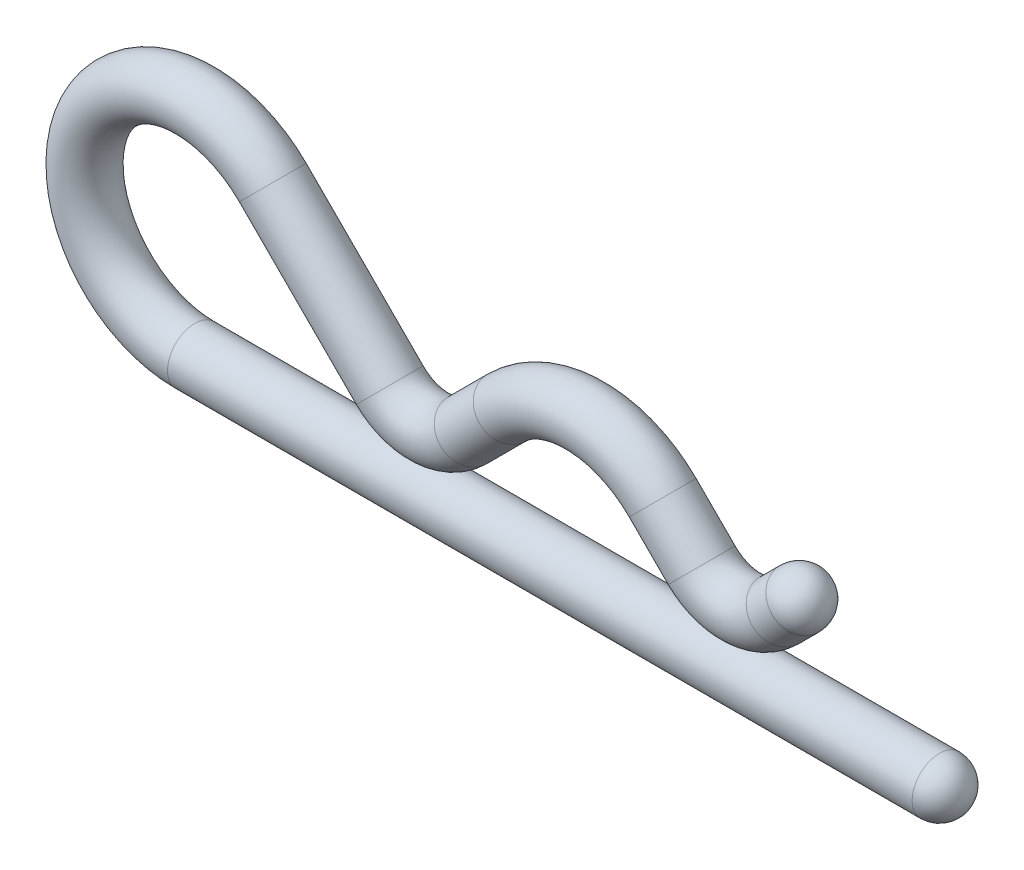
SolidWorks part; units mm, degrees
ref_plane "Front Plane" through (0, 0, 0) normal (0, 0, 1) x (1, 0, 0)
ref_plane "Top Plane" through (0, 0, 0) normal (0, 1, 0) x (1, 0, 0)
ref_plane "Right Plane" through (0, 0, 0) normal (1, 0, 0) x (0, 0, -1)
sketch "Sketch1" plane through (0, 0, 0) normal (0, 0, 1) x (1, 0, 0)
  line L0 (0, 0) -> (-28, 0)
  line L1 (-25.1716, 6.8284) -> (-20.9289, 2.5858)
  line L2 (-18.1005, 2.5858) -> (-16.6863, 4)
  line L3 (-11.0294, 4) -> (-9.6152, 2.5858)
  line L4 (-6.7868, 2.5858) -> (-5.3726, 4)
  arc A0 (-28, 0) -> (-25.1716, 6.8284) centre (-28, 4) cw
  arc A1 (-20.9289, 2.5858) -> (-18.1005, 2.5858) centre (-19.5147, 4) ccw
  arc A2 (-16.6863, 4) -> (-11.0294, 4) centre (-13.8579, 1.1716) cw
  arc A3 (-9.6152, 2.5858) -> (-6.7868, 2.5858) centre (-8.201, 4) ccw
  point P14 (-4.2585, 5.7728)
  point P15 (-6.7057, 5.4115)
  point P17 (0, 0)
  point P18 (0, 0)
  point P19 (0, 0)
  point P20 (0, 0)
  point P21 (0, 0)
  point P22 (-20.9289, 2.5858)
  point P23 (-20.9289, 2.5858)
  point P24 (-16.6863, 4)
  point P25 (-25.1716, 6.8284)
  point P26 (-13.8579, 1.1716)
  dimension "D1" = 2
  dimension "D2" = 4
  dimension "D7" = 4
  dimension "D8" = 2
  dimension "D3" = 45
  dimension "D4" = 2
  dimension "D5" = 4
  dimension "D6" = 28
  dimension "D9" = 1.1716
sketch "Sketch2" plane through (0, 0, 0) normal (1, 0, 0) x (0, 0, -1)
  circle A0 centre (0, 0) radius 0.99
  dimension "D1" = 1.98
sweep "Sweep3" add profiles "Sketch2" path "Sketch1"
fillet "Fillet1" radius 0.99 2 edges at (0, 0, -0.99) (-5.3726, 4, -0.99)
